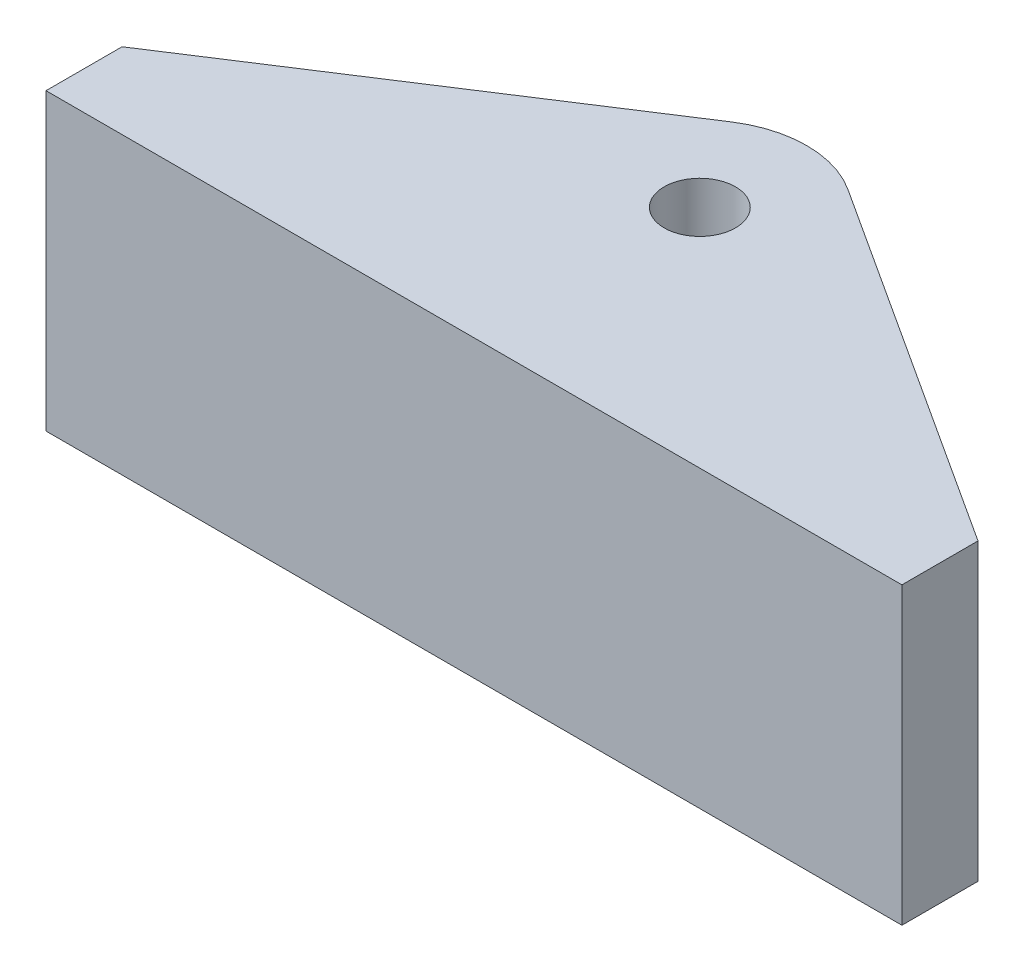
SolidWorks part; units mm, degrees
material "Cast Alloy Steel"
ref_plane "Front Plane" through (0, 0, 0) normal (0, 0, 1) x (1, 0, 0)
ref_plane "Top Plane" through (0, 0, 0) normal (0, 1, 0) x (1, 0, 0)
ref_plane "Right Plane" through (0, 0, 0) normal (1, 0, 0) x (0, 0, -1)
sketch "Sketch1" plane through (0, 0, 0) normal (0, 1, 0) x (1, 0, 0)
  line L0 (0, 5.08) -> (24.6907, 21.0767)
  line L1 (0, 0) -> (57.15, 0)
  line L2 (0, 0) -> (0, 5.08)
  line L4 (57.15, 0) -> (57.15, 5.08)
  line L5 (57.15, 5.08) -> (32.4593, 21.0767)
  circle A0 centre (28.575, 15.0813) radius 2.3813
  arc A1 (32.4593, 21.0767) -> (24.6907, 21.0767) centre (28.575, 15.0813) ccw
  point P7 (23.4059, 21.1554)
  point P8 (0, 0)
  dimension "D1" = 57.15
  dimension "D2" = 4.7625
  dimension "D5" = 28.575
  dimension "D6" = 4.7625
  dimension "D3" = 15.0812
  dimension "D4" = 5.08
extrude "Boss-Extrude1" add sketch "Sketch1" against normal blind 19.685
